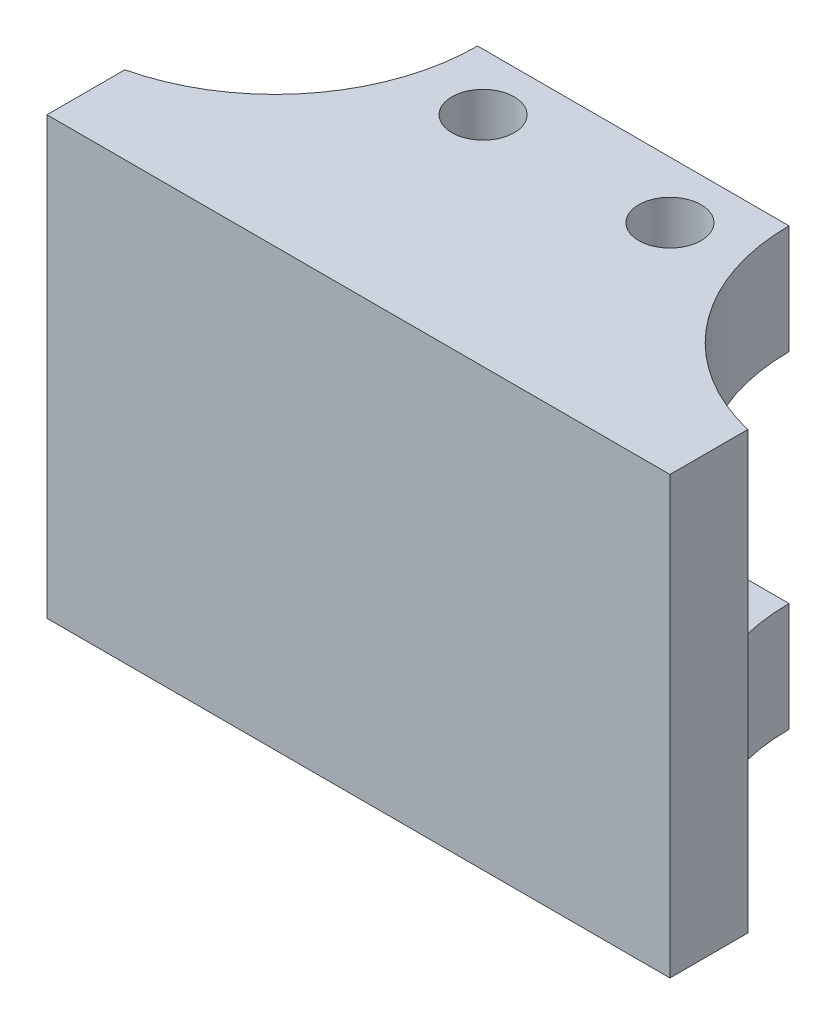
SolidWorks part; units mm, degrees
ref_plane "Front Plane" through (0, 0, 0) normal (0, 0, 1) x (1, 0, 0)
ref_plane "Top Plane" through (0, 0, 0) normal (0, 1, 0) x (1, 0, 0)
ref_plane "Right Plane" through (0, 0, 0) normal (1, 0, 0) x (0, 0, -1)
sketch "Sketch2" plane through (0, 0, 0) normal (0, 0, 1) x (1, 0, 0)
  line L1 (-200, 140) -> (200, 140)
  line L2 (-200, 140) -> (-200, -140)
  line L3 (-200, -140) -> (200, -140)
  line L4 (200, 140) -> (200, -140)
  point P7 (44.1899, -86.0115)
  dimension "D1" = 400
  dimension "D2" = 280
  dimension "D3" = 200
  dimension "D4" = 140
extrude "Boss-Extrude1" add sketch "Sketch2" along normal blind 50
sketch "Sketch4" plane through (0, 0, 0) normal (0, 1, 0) x (1, 0, 0)
  line L1 (-100, 126.4702) -> (100, 126.4702)
  line L3 (-100, 0) -> (100, 0)
  line L5 (-200, 0) -> (-100, 0)
  line L6 (0, 126.4702) -> (0, -21.7626) construction
  line L7 (200, 0) -> (100, 0)
  arc A0 (-200, 0) -> (-100, 126.4702) centre (-229.9736, 126.4702) ccw
  arc A1 (200, 0) -> (100, 126.4702) centre (229.9736, 126.4702) cw
  point P3 (0, 0)
  point P5 (0, 0)
  point P12 (0, 126.4702)
extrude "Boss-Extrude2" add sketch "Sketch4" along normal blind 140 and the other way blind 140
sketch "Sketch5" plane through (0, 0, 0) normal (1, 0, 0) x (0, 0, -1)
  line L0 (126.4702, -140) -> (126.4702, 140) construction
  line L1 (126.4702, 70) -> (0, 70)
  line L2 (126.4702, 70) -> (126.4702, -70)
  line L3 (126.4702, -70) -> (0, -70)
  line L4 (0, 70) -> (0, -70)
  line L5 (0, -140) -> (0, 140) construction
  dimension "D1" = 140
  dimension "D2" = 70
extrude "Cut-Extrude1" cut sketch "Sketch5" against normal blind 200 and the other way blind 200
sketch "Sketch6" plane through (0, 0, 0) normal (0, 1, 0) x (1, 0, 0)
  line L0 (200, -50) -> (-200, -50) construction
  circle A0 centre (-60, 90) radius 20
  circle A1 centre (60, 90) radius 20
  point P7 (0, 0)
  dimension "D1" = 40
  dimension "D2" = 40
  dimension "D3" = 60
  dimension "D4" = 60
  dimension "D5" = 140
  dimension "D6" = 140
extrude "Cut-Extrude2" cut sketch "Sketch6" against normal blind 200 and the other way blind 200
